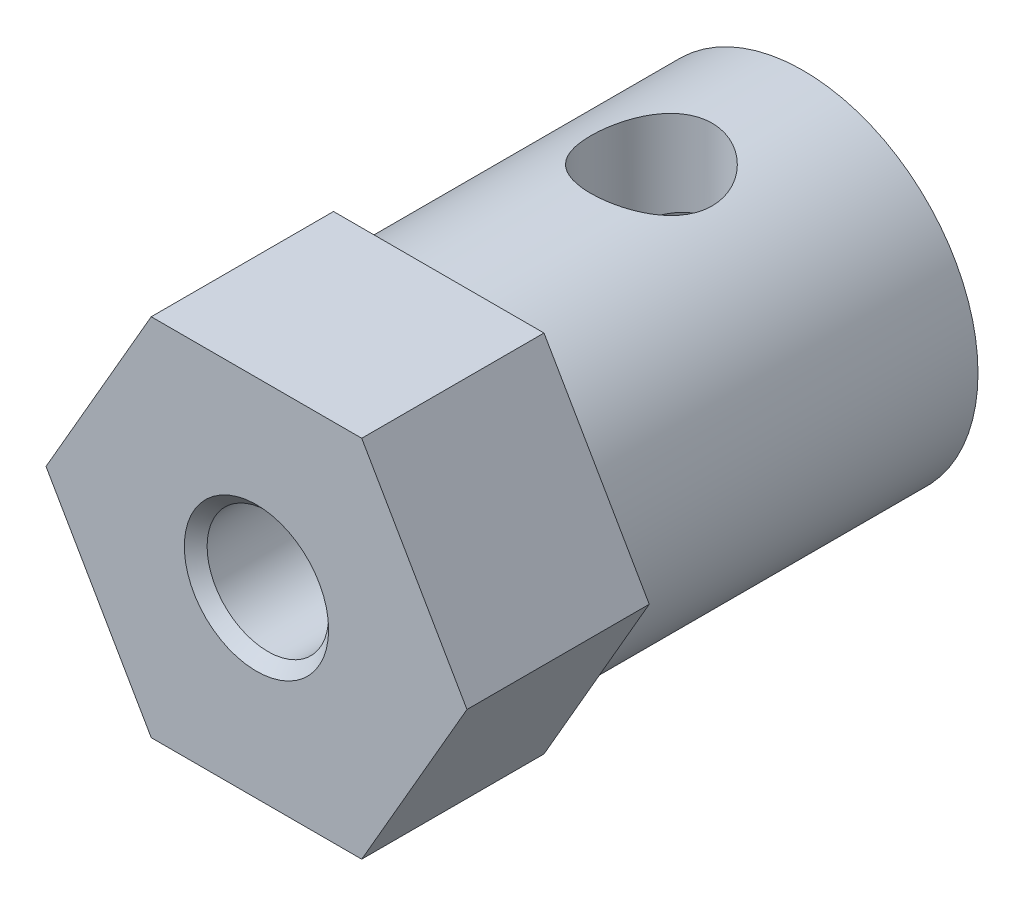
SolidWorks part; units mm, degrees
ref_plane "前视基准面" through (0, 0, 0) normal (0, 0, 1) x (1, 0, 0)
ref_plane "上视基准面" through (0, 0, 0) normal (0, 1, 0) x (1, 0, 0)
ref_plane "右视基准面" through (0, 0, 0) normal (1, 0, 0) x (0, 0, -1)
other "Configuration Table"
ref_plane "基准面1" through (0, 0, 6) normal (0, 0, 1) x (1, 0, 0)
sketch "草图1" plane through (0, 0, 6) normal (0, 0, 1) x (1, 0, 0)
  line L0 (-3.4641, -6) -> (3.4641, -6)
  line L1 (3.4641, -6) -> (6.9282, 0)
  line L2 (6.9282, 0) -> (3.4641, 6)
  line L3 (3.4641, 6) -> (-3.4641, 6)
  line L4 (-3.4641, 6) -> (-6.9282, 0)
  line L5 (-6.9282, 0) -> (-3.4641, -6)
extrude "凸台-拉伸1" add sketch "草图1" against normal blind 6
sketch "草图2" plane through (0, 0, 0) normal (0, 1, 0) x (1, 0, 0)
  line L0 (5.75, 12) -> (0, 12)
  line L1 (0, 12) -> (0, 0)
  line L2 (0, 0) -> (5.75, 0)
  line L3 (5.75, 0) -> (5.75, 12)
  line L4 (0, 12) -> (0, 0) construction
  line L5 (-55, -6) -> (55, -6) construction
  dimension "D1" = 5.75
  dimension "D2" = 18
revolve "旋转1" add sketch "草图2" angle 360 about L4
hole_wizard "M4 六角头机械螺钉的柱形沉头孔1" positions "草图4" profile "草图3" counterbore size "M3" standard "ANSI Metric"
sketch "草图4" plane through (0, 0, -12) normal (0, 0, -1) x (-1, 0, 0)
  point P0 (0, 0)
sketch "草图3" plane through (0, 0, -12) normal (1, 0, 0) x (0, 1, 0)
  line L0 (0, 0) -> (0, 18)
  line L1 (0, 18) -> (2, 18)
  line L3 (2, 18) -> (2, 12)
  line L4 (2, 12) -> (3, 12)
  line L5 (3, 12) -> (3, 0)
  line L7 (3, 0) -> (0, 0)
  line L11 (0, -6.35) -> (0, 107.95) construction
  dimension "通孔孔直径" = 4
  dimension "通孔孔深度" = 18
  dimension "柱形沉头孔直径" = 6
  dimension "柱形沉头孔深度" = 12
ref_plane "基准面2" through (0, 5.75, 0) normal (0, 1, 0) x (1, 0, 0)
sketch "草图7" plane through (0, 5.75, 0) normal (0, 1, 0) x (1, 0, 0)
  line L0 (0, 12) -> (0, -6) construction
  line L1 (3, 12) -> (-3, 12) construction
  line L2 (-55, -6) -> (55, -6) construction
  line L3 (5.75, 12) -> (-5.75, 12) construction
  circle A0 centre (0, 7) radius 2
  point P7 (0, 7)
  dimension "D2" = 4
  dimension "D1" = 5
extrude "切除-拉伸1" cut sketch "草图7" against normal through all
chamfer "倒角1" distance 0.375 angle 45 1 edges at (-2, 0, 6)
